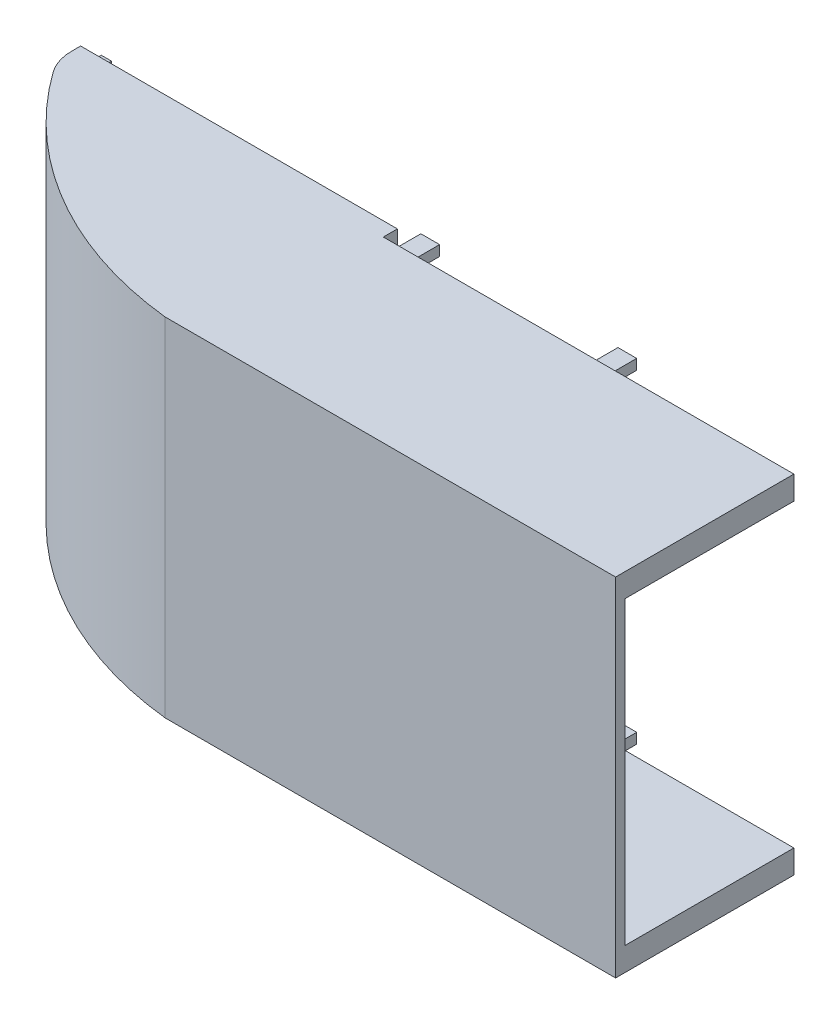
SolidWorks part; units mm, degrees
ref_plane "Alzado" through (0, 0, 0) normal (0, 0, 1) x (1, 0, 0)
ref_plane "Planta" through (0, 0, 0) normal (0, 1, 0) x (1, 0, 0)
ref_plane "Vista lateral" through (0, 0, 0) normal (1, 0, 0) x (0, 0, -1)
sketch "Croquis1" plane through (0, 0, 0) normal (0, 0, 1) x (1, 0, 0)
  line L1 (-59, -37) -> (59, -37)
  line L2 (-59, -37) -> (-59, 37)
  line L3 (-59, 37) -> (59, 37)
  line L4 (59, -37) -> (59, 37)
  line L5 (-59, -37) -> (59, 37) construction
  line L6 (-59, 37) -> (59, -37) construction
  point P0 (0, 0)
extrude "Saliente-Extruir1" add sketch "Croquis1" along normal blind 36
sketch "Croquis2" plane through (59, 0, 0) normal (1, 0, 0) x (0, 0, -1)
  line L0 (-36, 32) -> (0, 32)
  line L1 (-36, -37) -> (-36, 37) construction
  line L2 (0, -37) -> (0, 37) construction
  line L3 (0, 32) -> (0, -32)
  line L4 (0, -32) -> (-36, -32)
  line L5 (-36, -32) -> (-36, 32)
  line L6 (-36, 37) -> (0, 37) construction
  line L7 (-36, -37) -> (0, -37) construction
  dimension "D1" = 5
  dimension "D2" = 5
extrude "Cortar-Extruir1" cut sketch "Croquis2" against normal blind 120
sketch "Croquis6" plane through (0, -37, 0) normal (0, -1, 0) x (1, 0, 0)
  line L0 (-59, 0) -> (-59, 36)
  line L1 (-59, 36) -> (0, 36)
  line L2 (-59, 36) -> (59, 36) construction
  arc A0 (-59, 0) -> (0, 36) centre (8.6236, -44.4803) cw
extrude "Cortar-Extruir3" cut sketch "Croquis6" against normal through all from surface at 0 starting at face at (0, -37, 18)
sketch "Croquis7" plane through (0, 32, 0) normal (0, -1, 0) x (1, 0, 0)
  line L0 (0, 36) -> (59, 36)
  line L1 (59, 36) -> (59, 34)
  line L2 (59, 36) -> (59, 0) construction
  line L3 (59, 34) -> (14, 34)
  line L4 (14, 34) -> (-54, 6)
  line L5 (-54, 6) -> (-54, 0)
  line L6 (-59, 0) -> (59, 0) construction
  line L7 (-54, 0) -> (-59, 0)
  arc A0 (-59, 0) -> (0, 36) centre (8.6236, -44.4803) cw
extrude "Saliente-Extruir2" add sketch "Croquis7" along normal blind 64
sketch "Croquis8" plane through (0, 32, 0) normal (0, -1, 0) x (1, 0, 0)
  line L1 (14, 34) -> (-46.9372, 8.9082)
  arc A0 (14, 34) -> (-46.9372, 8.9082) centre (10.0292, -42.8975) ccw
extrude "Cortar-Extruir4" cut sketch "Croquis8" along normal blind 9
sketch "Croquis13" plane through (0, -32, 0) normal (0, 1, 0) x (1, 0, 0)
  line L0 (14, -34) -> (-46.9363, -8.9086)
  arc A0 (-46.9363, -8.9086) -> (14, -34) centre (10.0297, 42.8976) ccw
extrude "Cortar-Extruir5" cut sketch "Croquis13" along normal blind 9
sketch "Croquis17" plane through (0, 0, 0) normal (0, 0, -1) x (-1, 0, 0)
  line L0 (-59, 37) -> (-59, 32)
  line L1 (-59, 32) -> (54, 32)
  line L2 (54, 32) -> (54, -32)
  line L3 (54, -32) -> (-59, -32)
  line L4 (-59, -32) -> (-59, -37)
  line L5 (-59, -37) -> (59, -37)
  line L6 (59, -37) -> (59, 37)
  line L7 (59, 37) -> (-59, 37)
extrude "Saliente-Extruir4" add sketch "Croquis17" along normal blind 5
sketch "Croquis14" plane through (0, -37, 0) normal (0, -1, 0) x (1, 0, 0)
  line L0 (59, -2) -> (59, -5)
  line L1 (59, 36) -> (59, -5) construction
  line L3 (8.5, -5) -> (8.5, -2)
  line L5 (59, -5) -> (-59, -5) construction
  line L6 (59, 36) -> (59, -5) construction
  line L7 (8.5, -5) -> (59, -5)
  line L8 (8.5, -2) -> (59, -2)
extrude "Cortar-Extruir7" cut sketch "Croquis14" against normal blind 74
sketch "Croquis15" plane through (0, 0, -2) normal (0, 0, -1) x (-1, 0, 0)
  line L0 (-59, 37) -> (-8.5, 37) construction
  line L1 (-56.5, 35.6) -> (-52.5, 35.6)
  line L2 (-56.5, 35.6) -> (-56.5, 33.4)
  line L3 (-56.5, 33.4) -> (-52.5, 33.4)
  line L4 (-52.5, 35.6) -> (-52.5, 33.4)
  line L5 (-56.5, 35.6) -> (-52.5, 33.4) construction
  line L6 (-56.5, 33.4) -> (-52.5, 35.6) construction
  line L7 (-56.5, -33.4) -> (-52.5, -33.4)
  line L8 (-56.5, -33.4) -> (-56.5, -35.6)
  line L9 (-56.5, -35.6) -> (-52.5, -35.6)
  line L10 (-52.5, -33.4) -> (-52.5, -35.6)
  line L11 (-56.5, -33.4) -> (-52.5, -35.6) construction
  line L12 (-56.5, -35.6) -> (-52.5, -33.4) construction
  line L13 (-14.5, 35.6) -> (-10.5, 35.6)
  line L14 (-14.5, 35.6) -> (-14.5, 33.4)
  line L15 (-14.5, 33.4) -> (-10.5, 33.4)
  line L16 (-10.5, 35.6) -> (-10.5, 33.4)
  line L17 (-14.5, 35.6) -> (-10.5, 33.4) construction
  line L18 (-14.5, 33.4) -> (-10.5, 35.6) construction
  line L19 (-14.5, -33.4) -> (-10.5, -33.4)
  line L20 (-14.5, -33.4) -> (-14.5, -35.6)
  line L21 (-14.5, -35.6) -> (-10.5, -35.6)
  line L22 (-10.5, -33.4) -> (-10.5, -35.6)
  line L23 (-14.5, -33.4) -> (-10.5, -35.6) construction
  line L24 (-14.5, -35.6) -> (-10.5, -33.4) construction
  line L25 (55.4, -30.5) -> (57.6, -30.5)
  line L26 (55.4, -30.5) -> (55.4, -34.5)
  line L27 (55.4, -34.5) -> (57.6, -34.5)
  line L28 (57.6, -30.5) -> (57.6, -34.5)
  line L29 (55.4, -30.5) -> (57.6, -34.5) construction
  line L30 (55.4, -34.5) -> (57.6, -30.5) construction
  line L31 (55.4, 34.5) -> (57.6, 34.5)
  line L32 (55.4, 34.5) -> (55.4, 30.5)
  line L33 (55.4, 30.5) -> (57.6, 30.5)
  line L34 (57.6, 34.5) -> (57.6, 30.5)
  line L35 (55.4, 34.5) -> (57.6, 30.5) construction
  line L36 (55.4, 30.5) -> (57.6, 34.5) construction
  line L37 (-59, 37) -> (-59, 32) construction
  line L38 (-59, -37) -> (-8.5, -37) construction
  line L39 (59, 37) -> (-8.5, 37) construction
  line L40 (59, -37) -> (59, 37) construction
  line L41 (-8.5, -37) -> (59, -37) construction
  point P0 (-54.5, 34.5)
  point P5 (-12.5, 34.5)
  point P10 (-54.5, -34.5)
  point P16 (-12.5, -34.5)
  point P21 (56.5, -32.5)
  point P26 (56.5, 32.5)
  dimension "D1" = 1.4
  dimension "D2" = 2.5
  dimension "D3" = 1.4
  dimension "D4" = 1.4
  dimension "D5" = 1.4
  dimension "D6" = 2.5
  dimension "D7" = 1.4
  dimension "D8" = 2.5
extrude "Saliente-Extruir3" add sketch "Croquis15" along normal blind 6
fillet "Redondeo1" radius 10 1 edges at (-59, 0, 0)
sketch "Croquis19" plane through (59, 0, 0) normal (1, 0, 0) x (0, 0, -1)
  line L0 (2, 37) -> (2, 32)
  line L1 (2, 32) -> (-34, 32)
  line L2 (-34, 32) -> (-34, -32)
  line L3 (-34, -32) -> (2, -32)
  line L4 (2, -32) -> (2, -37)
  line L5 (2, -37) -> (-36, -37)
  line L6 (-36, -37) -> (-36, 37)
  line L7 (-36, 37) -> (2, 37)
extrude "Saliente-Extruir5" add sketch "Croquis19" along normal blind 37
sketch "Croquis21" plane through (-54, 0, 0) normal (1, 0, 0) x (0, 0, -1)
  line L0 (5, -17.4963) -> (5, 17.5037)
  line L1 (5, 32) -> (5, -32) construction
  line L2 (5, 17.5037) -> (-3, 17.5037)
  line L3 (-3, 17.5037) -> (-3, -17.4963)
  line L4 (-3, -17.4963) -> (5, -17.4963)
  point P5 (5, 0.0037)
extrude "Saliente-Extruir6" add sketch "Croquis21" along normal blind 5
sketch "Croquis22" plane through (-49, 0, 0) normal (1, 0, 0) x (0, 0, -1)
  line L0 (5, 17.5037) -> (5, -17.4963)
  line L1 (5, -17.4963) -> (2.1, -17.4963)
  line L2 (-3, -17.4963) -> (5, -17.4963) construction
  line L3 (2.1, -17.4963) -> (2.1, 17.5037)
  line L4 (5, 17.5037) -> (-3, 17.5037) construction
  line L5 (2.1, 17.5037) -> (5, 17.5037)
extrude "Cortar-Extruir8" cut sketch "Croquis22" against normal blind 5
sketch "Croquis23" plane through (-54, 0, 0) normal (1, 0, 0) x (0, 0, -1)
  line L2 (-3, 17.5037) -> (-3, -17.4963)
  line L5 (-3, 17.5037) -> (-6.8, 17.5037)
  line L6 (-6.8, 17.5037) -> (-6.8, -17.4963)
  line L7 (-6.8, -17.4963) -> (-3, -17.4963)
extrude "Saliente-Extruir7" add sketch "Croquis23" along normal blind 1.9
